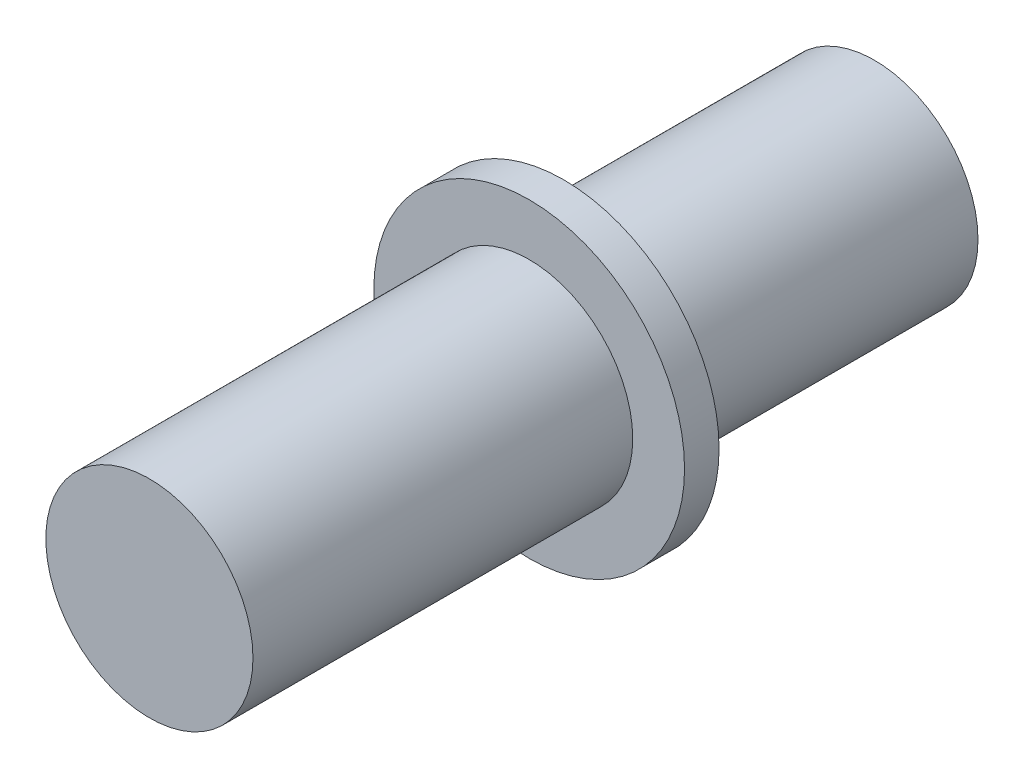
SolidWorks part; units mm, degrees
ref_plane "Front Plane" through (0, 0, 0) normal (0, 0, 1) x (1, 0, 0)
ref_plane "Top Plane" through (0, 0, 0) normal (0, 1, 0) x (1, 0, 0)
ref_plane "Right Plane" through (0, 0, 0) normal (1, 0, 0) x (0, 0, -1)
sketch "Sketch1" plane through (0, 0, 0) normal (0, 0, 1) x (1, 0, 0)
  circle A0 centre (0, 0) radius 6
extrude "Boss-Extrude1" add sketch "Sketch1" along normal blind 42
sketch "Sketch2" plane through (0, 0, 42) normal (0, 0, 1) x (1, 0, 0)
  circle A0 centre (0, 0) radius 9
extrude "Boss-Extrude2" add sketch "Sketch2" along normal blind 2 from offset 24
